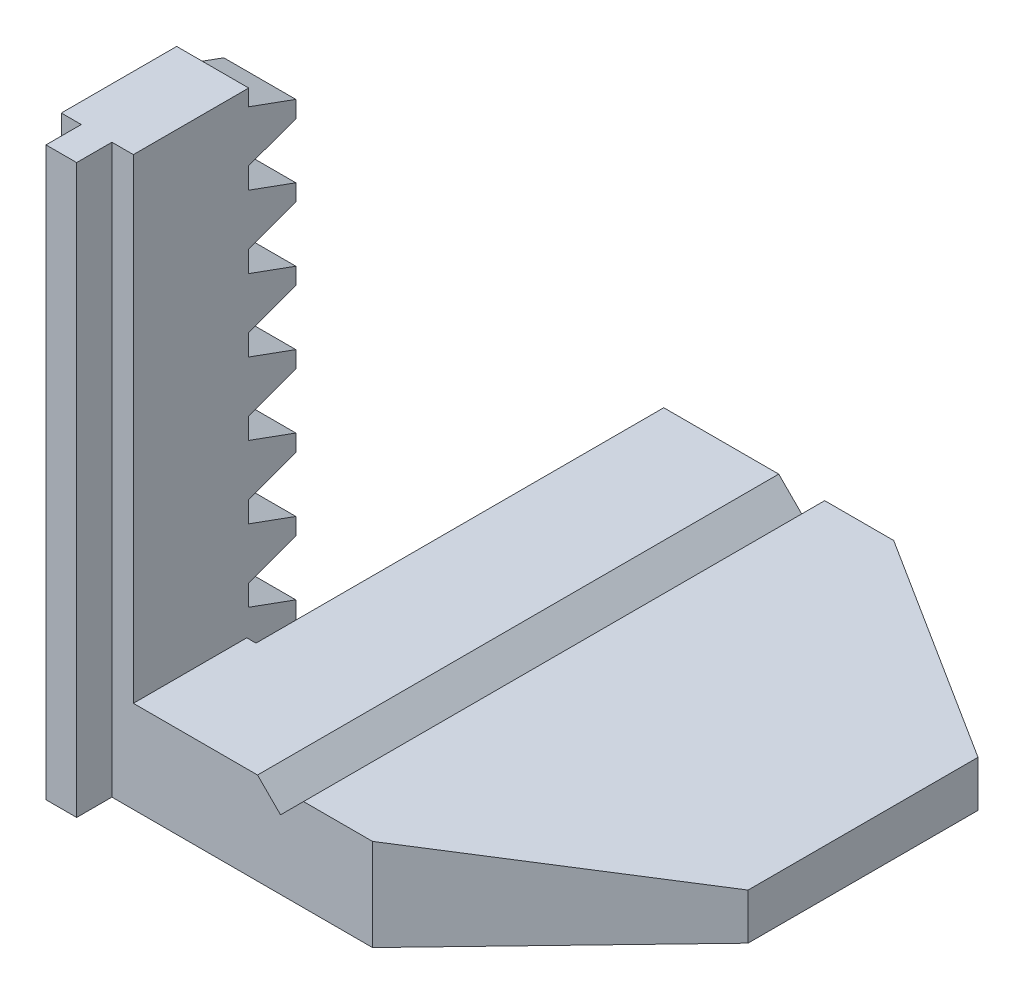
SolidWorks part; units mm, degrees
ref_plane "Front Plane" through (0, 0, 0) normal (0, 0, 1) x (1, 0, 0)
ref_plane "Top Plane" through (0, 0, 0) normal (0, 1, 0) x (1, 0, 0)
ref_plane "Right Plane" through (0, 0, 0) normal (1, 0, 0) x (0, 0, -1)
ref_plane "Plane1" through (209.7, 0, 0) normal (1, 0, 0) x (0, 0, -1)
ref_plane "Plane2" through (211, 0, 0) normal (1, 0, 0) x (0, 0, -1)
ref_plane "Plane3" through (214.4, 0, 0) normal (1, 0, 0) x (0, 0, -1)
ref_plane "Plane4" through (215, 0, 0) normal (1, 0, 0) x (0, 0, -1)
sketch "Sketch1" plane through (209.7, 0, 0) normal (1, 0, 0) x (0, 0, -1)
  line L0 (-318, -6) -> (-318, 31)
  line L1 (-318, 31) -> (-310.475, 31)
  line L2 (-310.475, 31) -> (-310.475, 30.0599)
  line L3 (-310.475, 30.0599) -> (-307.4, 28.9407)
  line L4 (-307.4, 28.9407) -> (-307.4, 27.608)
  line L5 (-307.4, 27.608) -> (-310.475, 26.4888)
  line L6 (-310.475, 26.4888) -> (-310.475, 25.3475)
  line L7 (-310.475, 25.3475) -> (-307.4, 24.2283)
  line L8 (-307.4, 24.2283) -> (-307.4, 22.8956)
  line L9 (-307.4, 22.8956) -> (-310.475, 21.7764)
  line L10 (-310.475, 21.7764) -> (-310.475, 20.6351)
  line L11 (-310.475, 20.6351) -> (-307.4, 19.5159)
  line L12 (-307.4, 19.5159) -> (-307.4, 18.1832)
  line L13 (-307.4, 18.1832) -> (-310.475, 17.064)
  line L14 (-310.475, 17.064) -> (-310.475, 15.9227)
  line L15 (-310.475, 15.9227) -> (-307.4, 14.8035)
  line L16 (-307.4, 14.8035) -> (-307.4, 13.4708)
  line L17 (-307.4, 13.4708) -> (-310.475, 12.3516)
  line L18 (-310.475, 12.3516) -> (-310.475, 11.2103)
  line L19 (-310.475, 11.2103) -> (-307.4, 10.0911)
  line L20 (-307.4, 10.0911) -> (-307.4, 8.7584)
  line L21 (-307.4, 8.7584) -> (-310.475, 7.6392)
  line L22 (-310.475, 7.6392) -> (-310.475, 6.4979)
  line L23 (-310.475, 6.4979) -> (-307.4, 5.3787)
  line L24 (-307.4, 5.3787) -> (-307.4, 4.0461)
  line L25 (-307.4, 4.0461) -> (-310.475, 2.9268)
  line L26 (-310.475, 2.9268) -> (-310.475, 1.7855)
  line L27 (-310.475, 1.7855) -> (-307.4, 0.6663)
  line L28 (-307.4, 0.6663) -> (-307.4, -0.6663)
  line L29 (-307.4, -0.6663) -> (-310.475, -1.7855)
  line L30 (-310.475, -1.7855) -> (-310.475, -2.9268)
  line L31 (-310.475, -2.9268) -> (-307.4, -4.0461)
  line L32 (-307.4, -4.0461) -> (-307.4, -5.3787)
  line L33 (-307.4, -5.3787) -> (-309.1069, -6)
  line L34 (-309.1069, -6) -> (-318, -6)
extrude "Boss-Extrude1" add sketch "Sketch1" along normal blind 4.7
sketch "Sketch2" plane through (211, 0, 0) normal (1, 0, 0) x (0, 0, -1)
  line L1 (-320.3, -6) -> (-317.9, -6)
  line L2 (-320.3, -6) -> (-320.3, 31)
  line L3 (-320.3, 31) -> (-317.9, 31)
  line L4 (-317.9, -6) -> (-317.9, 31)
extrude "Boss-Extrude2" add sketch "Sketch2" along normal blind 2
sketch "Sketch3" plane through (214.4, 0, 0) normal (1, 0, 0) x (0, 0, -1)
  line L1 (-318, -6) -> (-310.6, -6)
  line L2 (-318, -6) -> (-318, 0)
  line L3 (-318, 0) -> (-310.6, 0)
  line L4 (-310.6, -6) -> (-310.6, 0)
extrude "Boss-Extrude3" add sketch "Sketch3" along normal blind 0.8
sketch "Sketch4" plane through (215, 0, 0) normal (1, 0, 0) x (0, 0, -1)
  line L1 (-318, -6) -> (-287, -6)
  line L2 (-318, -6) -> (-318, 0)
  line L3 (-318, 0) -> (-287, 0)
  line L4 (-287, -6) -> (-287, 0)
extrude "Boss-Extrude4" add sketch "Sketch4" along normal blind 30
sketch "Sketch8" plane through (209.7, 0, 0) normal (1, 0, 0) x (0, 0, -1)
  line L0 (-307, -4.1716) -> (-310.475, -2.907)
  line L1 (-310.475, -2.907) -> (-310.475, -3.047)
  line L2 (-310.475, -3.047) -> (-307, -4.3116)
  line L3 (-307, -4.3116) -> (-307, -4.1716)
  line L4 (-307, -5.2532) -> (-310.475, -6.5178)
  line L5 (-310.475, -6.5178) -> (-310.475, -6.3778)
  line L6 (-310.475, -6.3778) -> (-307, -5.1132)
  line L7 (-307, -5.1132) -> (-307, -5.2532)
  line L8 (-307, 0.5408) -> (-310.475, 1.8054)
  line L9 (-310.475, 1.8054) -> (-310.475, 1.6654)
  line L10 (-310.475, 1.6654) -> (-307, 0.4008)
  line L11 (-307, 0.4008) -> (-307, 0.5408)
  line L12 (-307, -0.5408) -> (-310.475, -1.8054)
  line L13 (-310.475, -1.8054) -> (-310.475, -1.6654)
  line L14 (-310.475, -1.6654) -> (-307, -0.4008)
  line L15 (-307, -0.4008) -> (-307, -0.5408)
  line L16 (-307, 5.2532) -> (-310.475, 6.5178)
  line L17 (-310.475, 6.5178) -> (-310.475, 6.3778)
  line L18 (-310.475, 6.3778) -> (-307, 5.1132)
  line L19 (-307, 5.1132) -> (-307, 5.2532)
  line L20 (-307, 4.1716) -> (-310.475, 2.907)
  line L21 (-310.475, 2.907) -> (-310.475, 3.047)
  line L22 (-310.475, 3.047) -> (-307, 4.3116)
  line L23 (-307, 4.3116) -> (-307, 4.1716)
  line L24 (-307, 9.9656) -> (-310.475, 11.2302)
  line L25 (-310.475, 11.2302) -> (-310.475, 11.0902)
  line L26 (-310.475, 11.0902) -> (-307, 9.8256)
  line L27 (-307, 9.8256) -> (-307, 9.9656)
  line L28 (-307, 8.884) -> (-310.475, 7.6194)
  line L29 (-310.475, 7.6194) -> (-310.475, 7.7594)
  line L30 (-310.475, 7.7594) -> (-307, 9.024)
  line L31 (-307, 9.024) -> (-307, 8.884)
  line L32 (-307, 14.678) -> (-310.475, 15.9426)
  line L33 (-310.475, 15.9426) -> (-310.475, 15.8026)
  line L34 (-310.475, 15.8026) -> (-307, 14.538)
  line L35 (-307, 14.538) -> (-307, 14.678)
  line L36 (-307, 13.5964) -> (-310.475, 12.3318)
  line L37 (-310.475, 12.3318) -> (-310.475, 12.4718)
  line L38 (-310.475, 12.4718) -> (-307, 13.7364)
  line L39 (-307, 13.7364) -> (-307, 13.5964)
  line L40 (-307, 19.3904) -> (-310.475, 20.655)
  line L41 (-310.475, 20.655) -> (-310.475, 20.515)
  line L42 (-310.475, 20.515) -> (-307, 19.2504)
  line L43 (-307, 19.2504) -> (-307, 19.3904)
  line L44 (-307, 18.3088) -> (-310.475, 17.0442)
  line L45 (-310.475, 17.0442) -> (-310.475, 17.1842)
  line L46 (-310.475, 17.1842) -> (-307, 18.4488)
  line L47 (-307, 18.4488) -> (-307, 18.3088)
  line L48 (-307, 24.1027) -> (-310.475, 25.3673)
  line L49 (-310.475, 25.3673) -> (-310.475, 25.2274)
  line L50 (-310.475, 25.2274) -> (-307, 23.9628)
  line L51 (-307, 23.9628) -> (-307, 24.1027)
  line L52 (-307, 23.0211) -> (-310.475, 21.7565)
  line L53 (-310.475, 21.7565) -> (-310.475, 21.8965)
  line L54 (-310.475, 21.8965) -> (-307, 23.1611)
  line L55 (-307, 23.1611) -> (-307, 23.0211)
  line L56 (-307, 28.8151) -> (-310.475, 30.0797)
  line L57 (-310.475, 30.0797) -> (-310.475, 29.9397)
  line L58 (-310.475, 29.9397) -> (-307, 28.6751)
  line L59 (-307, 28.6751) -> (-307, 28.8151)
  line L60 (-307, 27.7335) -> (-310.475, 26.4689)
  line L61 (-310.475, 26.4689) -> (-310.475, 26.6089)
  line L62 (-310.475, 26.6089) -> (-307, 27.8735)
  line L63 (-307, 27.8735) -> (-307, 27.7335)
extrude "Cut-Extrude4" cut sketch "Sketch8" along normal mid plane 9.4
sketch "Sketch9" plane through (215, 0, 0) normal (1, 0, 0) x (0, 0, -1)
  line L0 (-287, -6) -> (-284, -6)
  line L1 (-284, -6) -> (-284, 0)
  line L2 (-284, 0) -> (-287, 0)
  line L3 (-287, 0) -> (-287, -6)
extrude "Boss-Extrude6" add sketch "Sketch9" along normal blind 30
sketch "Sketch10" plane through (0, 0, 0) normal (0, 0, 1) x (1, 0, 0)
  line L0 (227.5, -6.5) -> (246.5, -2.7)
  line L1 (246.5, -2.7) -> (246.5, -6.5)
  line L2 (246.5, -6.5) -> (227.5, -6.5)
extrude "Cut-Extrude5" cut sketch "Sketch10" along normal through all
sketch "Sketch11" plane through (0, 0, 0) normal (0, 0, 1) x (1, 0, 0)
  line L0 (222, 0.5) -> (226, 0.5)
  line L1 (226, 0.5) -> (224, -1.5)
  line L2 (224, -1.5) -> (222, 0.5)
extrude "Cut-Extrude6" cut sketch "Sketch11" along normal through all
sketch "Sketch12" plane through (0, 0, 0) normal (0, 1, 0) x (1, 0, 0)
  line L0 (228.125, -319.1875) -> (246.5, -307.55)
  line L1 (246.5, -307.55) -> (246.5, -319.1875)
  line L2 (246.5, -319.1875) -> (228.125, -319.1875)
  line L3 (228.125, -282.8125) -> (246.5, -294.45)
  line L4 (246.5, -294.45) -> (246.5, -282.8125)
  line L5 (246.5, -282.8125) -> (228.125, -282.8125)
extrude "Cut-Extrude7" cut sketch "Sketch12" along normal mid plane 13
